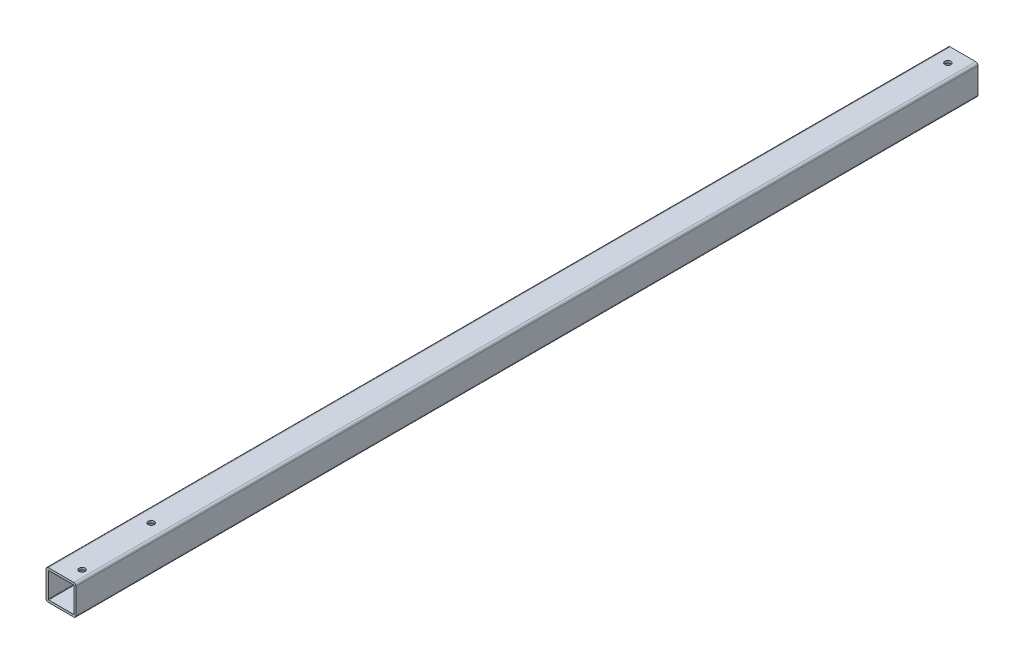
SolidWorks part; units mm, degrees
ref_plane "Front Plane" through (0, 0, 0) normal (0, 0, 1) x (1, 0, 0)
ref_plane "Top Plane" through (0, 0, 0) normal (0, 1, 0) x (1, 0, 0)
ref_plane "Right Plane" through (0, 0, 0) normal (1, 0, 0) x (0, 0, -1)
sketch "Sketch1" plane through (0, 0, 0) normal (0, 0, 1) x (1, 0, 0)
  line L1 (-20, 20) -> (20, 20)
  line L2 (-20, 20) -> (-20, -20)
  line L3 (-20, -20) -> (20, -20)
  line L4 (20, 20) -> (20, -20)
  line L5 (-20, 20) -> (20, -20) construction
  line L6 (-20, -20) -> (20, 20) construction
  point P0 (0, 0)
  dimension "D1" = 40
  dimension "D2" = 40
extrude "Extrude-Thin1" add sketch "Sketch1" along normal blind 1200 thin
fillet "Fillet1" radius 0.5 4 edges at (-17, -17, 600) (-17, 17, 600) (17, 17, 600) (17, -17, 600)
fillet "Fillet2" radius 3 4 edges at (20, -20, 600) (-20, -20, 600) (20, 20, 600) (-20, 20, 600)
hole_wizard "Ø8.0 (8) Diameter Hole1" positions "Sketch4" profile "Sketch3" hole size "Ø8.0" standard "ANSI Metric" end condition through all
sketch "Sketch4" plane through (0, 20, 0) normal (0, 1, 0) x (1, 0, 0)
  line L0 (0, 0) -> (0, -1200) construction
  line L1 (17, -1200) -> (-17, -1200) construction
  point P8 (0, -20)
  point P10 (0, -1080)
  dimension "D1" = 20
  dimension "D2" = 120
sketch "Sketch3" plane through (0, 20, 20) normal (1, 0, 0) x (0, 0, 1)
  line L0 (0, 0) -> (0, 40)
  line L1 (0, 40) -> (4, 40)
  line L2 (4, 40) -> (4, 0)
  line L5 (4, 0) -> (0, 0)
  line L11 (0, -6.35) -> (0, 107.95) construction
  dimension "Thru Hole Dia." = 8
  dimension "Thru Hole Depth" = 40
hole_wizard "Ø8.0 (8) Diameter Hole2" positions "Sketch6" profile "Sketch5" hole size "Ø8.0" standard "ANSI Metric" end condition through all
sketch "Sketch6" plane through (0, 20, 0) normal (0, 1, 0) x (1, 0, 0)
  line L0 (20, 0) -> (20, -1200) construction
  line L1 (17, -1200) -> (-17, -1200) construction
  point P0 (8, -1180)
  dimension "D1" = 12
  dimension "D2" = 20
sketch "Sketch5" plane through (8, 20, 1180) normal (1, 0, 0) x (0, 0, 1)
  line L0 (0, 0) -> (0, 40)
  line L1 (0, 40) -> (4, 40)
  line L2 (4, 40) -> (4, 0)
  line L5 (4, 0) -> (0, 0)
  line L11 (0, -6.35) -> (0, 107.95) construction
  dimension "Thru Hole Dia." = 8
  dimension "Thru Hole Depth" = 40
equation "\"a\"= \"Beam Profile@Plasma Beta.Assembly\""
equation "\"b\"= 3"
equation "\"L\"= \"Lenght@Plasma Beta.Assembly\""
equation "\"D2@Sketch1\"=\"a\""
equation "\"D1@Sketch1\"=\"a\""
equation "\"D1@Extrude-Thin1\"=\"L\""
equation "\"D5@Extrude-Thin1\"=\"b\""
equation "\"D1@Fillet2\"=\"b\""
